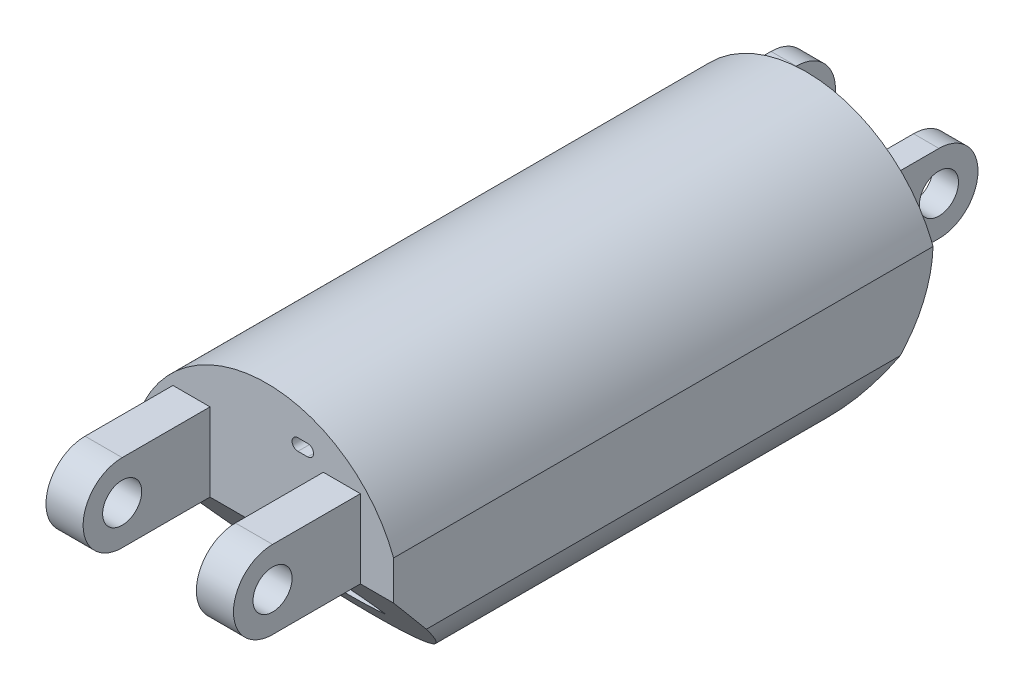
SolidWorks part; units mm, degrees
material "PET"
ref_plane "Front Plane" through (0, 0, 0) normal (0, 0, 1) x (1, 0, 0)
ref_plane "Top Plane" through (0, 0, 0) normal (0, 1, 0) x (1, 0, 0)
ref_plane "Right Plane" through (0, 0, 0) normal (1, 0, 0) x (0, 0, -1)
sketch "Sketch1" plane through (0, 0, 0) normal (0, 0, 1) x (1, 0, 0)
  line L0 (0, 0) -> (0, 5.08)
  line L3 (16.51, 5.08) -> (16.51, 0)
  arc A2 (0, 5.08) -> (16.51, 5.08) centre (8.255, 1.9756) cw
  arc A3 (0, 0) -> (16.51, 0) centre (8.255, 3.1044) ccw
  point P7 (8.255, -5.715)
  point P8 (8.255, 10.795)
extrude "Boss-Extrude1" add sketch "Sketch1" along normal mid plane 35.0838 contours A2 L3 A3 L0
sketch "Sketch2" plane through (0, 0, 0) normal (1, 0, 0) x (0, 0, -1)
  line L4 (15.875, 2.54) -> (-49984.125, 2.54) construction
  line L5 (17.5419, 5.08) -> (17.5419, 0) construction
  line L6 (-17.5419, 5.08) -> (-17.5419, 0) construction
  line L10 (0, -1000) -> (0, 49000) construction
  line L17 (-17.5419, 0) -> (-17.5419, 5.08) construction
  line L23 (17.5419, -5.715) -> (10.6151, -5.715)
  line L24 (17.5419, 2.54) -> (17.5419, -5.715)
  line L30 (-17.5419, 2.54) -> (-17.5419, -5.715)
  line L32 (-17.5419, -5.715) -> (-10.6151, -5.715)
  line L33 (-17.5419, -5.715) -> (17.5419, -5.715) construction
  line L34 (-10.6151, -5.715) -> (-17.5419, 2.54)
  line L35 (10.6151, -5.715) -> (17.5419, 2.54)
  line L36 (-17.5419, -5.715) -> (17.5419, -5.715) construction
  point P0 (-15.0884, 2.54)
  point P11 (17.5419, 2.54)
  point P14 (-17.5419, 2.54)
  dimension "D4" = 50
extrude "Cut-Extrude1" cut sketch "Sketch2" along normal through all
sketch "Sketch3" plane through (0, 0, 17.5419) normal (0, 0, 1) x (1, 0, 0)
  arc A0 (16.51, 5.08) -> (0, 5.08) centre (8.255, 1.9756) ccw construction
  arc A3 (16.51, 5.08) -> (0, 5.08) centre (8.255, 1.9756) ccw
  arc A5 (15.3213, 4.633) -> (1.1887, 4.633) centre (8.255, 1.9756) ccw
  arc A6 (5.024, 8.7987) -> (11.3659, 8.8543) centre (8.1936, 8.985) ccw
  arc A7 (14.9144, 0.2378) -> (1.7305, 0.2378) centre (8.3225, 3.9175) cw
  arc A9 (5.2791, -2.9913) -> (11.3659, -2.9913) centre (8.3225, -3.8959) cw
  dimension "D2" = 1.27
  dimension "D4" = 3.175
extrude "Cut-Extrude2" cut sketch "Sketch3" against normal through all
ref_plane "Plane1" through (11.43, 0, 0) normal (1, 0, 0) x (0, 0, -1)
sketch "Sketch4" plane through (11.43, 0, 0) normal (1, 0, 0) x (0, 0, -1)
  line L0 (-17.5419, 7.62) -> (-20.7169, 7.62)
  line L1 (-17.5419, 7.62) -> (-17.5419, 2.54)
  line L2 (-17.5419, 2.54) -> (-20.7169, 2.54)
  line L3 (-17.5419, 5.08) -> (-17.5419, 2.54) construction
  line L4 (-15.4106, 0) -> (15.4106, 0) construction
  arc A0 (-20.7169, 7.62) -> (-20.7169, 2.54) centre (-20.7169, 5.08) ccw
  circle A1 centre (-20.7169, 5.08) radius 1.27
  dimension "D2" = 2.54
  dimension "D1" = 5.08
  dimension "D3" = 3.175
  dimension "D4" = 2.54
extrude "Boss-Extrude2" add sketch "Sketch4" along normal mid plane 1.27
sketch "Sketch5" plane through (10.795, 0, 0) normal (-1, 0, 0) x (0, 0, 1)
  line L3 (17.5419, 7.62) -> (17.5419, 2.54)
  line L4 (17.5419, 2.54) -> (20.7169, 2.54)
  line L5 (20.7169, 7.62) -> (17.5419, 7.62)
  line L6 (17.5419, 7.62) -> (17.5419, 2.54)
  line L7 (17.5419, 2.54) -> (20.7169, 2.54)
  line L8 (20.7169, 7.62) -> (17.5419, 7.62)
  circle A0 centre (20.7169, 5.08) radius 1.27 construction
  arc A1 (20.7169, 2.54) -> (20.7169, 7.62) centre (20.7169, 5.08) ccw
  arc A2 (20.7169, 2.54) -> (20.7169, 7.62) centre (20.7169, 5.08) ccw
  circle A3 centre (20.7169, 5.08) radius 1.27
  dimension "D1" = 0
extrude "Boss-Extrude3" add sketch "Sketch5" along normal blind 1.27
ref_plane "Plane2" through (8.255, 0, 0) normal (1, 0, 0) x (0, 0, -1)
mirror "Mirror1" about plane through (8.255, 0, 0) normal (1, 0, 0) of "Boss-Extrude3", "Boss-Extrude2"
mirror "Mirror2" about plane through (0, 0, 0) normal (0, 0, 1) of "Mirror1", "Boss-Extrude3", "Boss-Extrude2"
sketch "Sketch6" plane through (9.525, 0, 0) normal (-1, 0, 0) x (0, 0, 1)
  line L3 (20.7169, 7.62) -> (17.5419, 7.62)
  line L4 (17.5419, 7.62) -> (17.5419, 2.54)
  line L5 (17.5419, 2.54) -> (20.7169, 2.54)
  line L6 (20.7169, 7.62) -> (17.5419, 7.62)
  line L7 (17.5419, 7.62) -> (17.5419, 2.54)
  line L8 (17.5419, 2.54) -> (20.7169, 2.54)
  circle A0 centre (20.7169, 5.08) radius 1.27 construction
  arc A1 (20.7169, 2.54) -> (20.7169, 7.62) centre (20.7169, 5.08) ccw
  arc A2 (20.7169, 2.54) -> (20.7169, 7.62) centre (20.7169, 5.08) ccw
  circle A3 centre (20.7169, 5.08) radius 1.27
  dimension "D1" = 0
extrude "Cut-Extrude3" cut sketch "Sketch6" against normal blind 0.635
sketch "Sketch7" plane through (12.065, 0, 0) normal (1, 0, 0) x (0, 0, -1)
  line L3 (-17.5419, 2.54) -> (-17.5419, 7.62)
  line L4 (-17.5419, 7.62) -> (-20.7169, 7.62)
  line L5 (-20.7169, 2.54) -> (-17.5419, 2.54)
  line L6 (-17.5419, 2.54) -> (-17.5419, 7.62)
  line L7 (-17.5419, 7.62) -> (-20.7169, 7.62)
  line L8 (-20.7169, 2.54) -> (-17.5419, 2.54)
  circle A0 centre (-20.7169, 5.08) radius 1.27 construction
  arc A1 (-20.7169, 7.62) -> (-20.7169, 2.54) centre (-20.7169, 5.08) ccw
  arc A2 (-20.7169, 7.62) -> (-20.7169, 2.54) centre (-20.7169, 5.08) ccw
  circle A3 centre (-20.7169, 5.08) radius 1.27
  dimension "D1" = 0
extrude "Boss-Extrude4" add sketch "Sketch7" along normal blind 0.381
mirror "Mirror3" about plane through (8.255, 0, 0) normal (1, 0, 0) of "Boss-Extrude4", "Cut-Extrude3"
mirror "Mirror4" about plane through (0, 0, 0) normal (0, 0, 1) of "Mirror3", "Cut-Extrude3", "Boss-Extrude4"
sketch "Sketch13" plane through (12.446, 0, 0) normal (1, 0, 0) x (0, 0, -1)
  line L0 (-20.7169, 2.54) -> (-17.5419, 2.54) construction
  line L1 (-17.5419, 7.62) -> (-23.2569, 7.62)
  line L2 (-17.5419, 7.62) -> (-17.5419, 2.54)
  line L3 (-17.5419, 2.54) -> (-23.2569, 2.54)
  line L4 (-23.2569, 7.62) -> (-23.2569, 2.54) construction
  arc A0 (-20.7169, 7.62) -> (-20.7169, 2.54) centre (-20.7169, 5.08) ccw construction
  arc A1 (-23.2569, 7.62) -> (-23.2569, 2.54) centre (-23.2569, 5.08) ccw
extrude "Boss-Extrude8" add sketch "Sketch13" against normal up to surface (2.286 mm away) up to face at (10.16, 5.08, 21.9869)
sketch "Sketch14" plane through (4.064, 0, 0) normal (-1, 0, 0) x (0, 0, 1)
  line L3 (17.5419, 2.54) -> (23.2569, 2.54)
  line L5 (17.5419, 7.62) -> (17.5419, 2.54)
  line L8 (17.5419, 7.62) -> (17.5419, 2.54)
  line L13 (17.5419, 2.54) -> (23.2569, 2.54)
  line L15 (23.2569, 7.62) -> (17.5419, 7.62)
  line L16 (23.2569, 7.62) -> (17.5419, 7.62)
  arc A1 (23.2569, 2.54) -> (23.2569, 7.62) centre (23.2569, 5.08) ccw
  arc A6 (23.2569, 2.54) -> (23.2569, 7.62) centre (23.2569, 5.08) ccw
  dimension "D1" = 0
extrude "Boss-Extrude9" add sketch "Sketch14" against normal up to surface (2.286 mm away) up to face at (6.35, 5.08, 19.7644)
ref_plane "Plane3" through (8.255, 0, 0) normal (1, 0, 0) x (0, 0, -1)
sketch "Sketch30" plane through (8.255, 0, 0) normal (1, 0, 0) x (0, 0, -1)
  line L3 (17.5419, 2.54) -> (20.7169, 2.54)
  line L4 (20.7169, 7.62) -> (17.5419, 7.62)
  line L5 (17.5419, 7.62) -> (17.5419, 2.54)
  line L6 (17.5419, 2.54) -> (20.7169, 2.54)
  line L7 (20.7169, 7.62) -> (17.5419, 7.62)
  line L9 (17.5419, 7.62) -> (17.5419, 2.54)
  arc A1 (20.7169, 2.54) -> (20.7169, 7.62) centre (20.7169, 5.08) ccw
  arc A2 (20.7169, 2.54) -> (20.7169, 7.62) centre (20.7169, 5.08) ccw
  circle A3 centre (20.7169, 5.08) radius 1.27
  circle A4 centre (20.7169, 5.08) radius 1.27
  dimension "D1" = 0
  dimension "D2" = 0
extrude "Cut-Extrude13" cut sketch "Sketch30" against normal blind 3.81 and the other way blind 3.81
sketch "Sketch31" plane through (12.446, 0, 0) normal (1, 0, 0) x (0, 0, -1)
  line L3 (17.5419, 2.54) -> (20.7169, 2.54)
  line L4 (20.7169, 7.62) -> (17.5419, 7.62)
  line L5 (17.5419, 7.62) -> (17.5419, 2.54)
  line L6 (17.5419, 2.54) -> (20.7169, 2.54)
  line L7 (20.7169, 7.62) -> (17.5419, 7.62)
  line L9 (17.5419, 7.62) -> (17.5419, 2.54)
  circle A1 centre (20.7169, 5.08) radius 1.27
  circle A2 centre (20.7169, 5.08) radius 1.27
  arc A3 (20.7169, 2.54) -> (20.7169, 7.62) centre (20.7169, 5.08) ccw
  arc A4 (20.7169, 2.54) -> (20.7169, 7.62) centre (20.7169, 5.08) ccw
  dimension "D1" = 0
  dimension "D2" = 0
extrude "Boss-Extrude17" add sketch "Sketch31" along normal blind 1.27
mirror "Mirror11" about plane through (8.255, 0, 0) normal (1, 0, 0) of "Boss-Extrude17"
sketch "Sketch32" plane through (0, 0, -17.5419) normal (0, 0, -1) x (-1, 0, 0)
  line L0 (-16.51, 2.54) -> (-13.716, 2.54) construction
  line L1 (-10.922, 3.048) -> (-5.588, 3.048) construction
  line L2 (-10.922, 3.048) -> (-10.922, 8.7376) construction
  line L3 (-10.922, 8.7376) -> (-5.588, 8.7376) construction
  line L4 (-5.588, 3.048) -> (-5.588, 8.7376) construction
  line L5 (-10.922, 3.048) -> (-5.588, 8.7376) construction
  line L6 (-10.922, 8.7376) -> (-5.588, 3.048) construction
  line L7 (-16.51, 2.54) -> (-13.716, 2.54)
  line L8 (-6.223, 8.3566) -> (-5.588, 8.3566) construction
  line L9 (-6.223, 8.7376) -> (-5.588, 8.7376)
  line L10 (-6.223, 7.9756) -> (-5.588, 7.9756)
  line L11 (-12.065, 2.54) -> (-4.445, 2.54) construction
  arc A0 (-6.223, 8.7376) -> (-6.223, 7.9756) centre (-6.223, 8.3566) ccw
  arc A1 (-5.588, 7.9756) -> (-5.588, 8.7376) centre (-5.588, 8.3566) ccw
  point P0 (-8.255, 5.8928)
  point P11 (-5.9055, 8.3566)
  point P19 (-8.255, 2.54)
  dimension "D1" = 5.6896
  dimension "D2" = 5.334
  dimension "D3" = 3.048
  dimension "D4" = 0.762
  dimension "D5" = 0.635
extrude "Cut-Extrude14" cut sketch "Sketch32" against normal blind 17.78 contours L10 A1 L9 A0
fillet "Fillet1" radius 7.62 2 edges at (1.397, 2.54, -17.5419) (15.113, 2.54, -17.5419)
sketch "Sketch33" plane through (8.255, 0, 0) normal (1, 0, 0) x (0, 0, -1)
  line L3 (-23.2569, 2.54) -> (-17.5419, 2.54)
  line L4 (-17.5419, 2.54) -> (-17.5419, 7.62)
  line L5 (-17.5419, 7.62) -> (-23.2569, 7.62)
  line L6 (-23.2569, 2.54) -> (-17.5419, 2.54)
  line L7 (-17.5419, 2.54) -> (-17.5419, 7.62)
  line L8 (-17.5419, 7.62) -> (-23.2569, 7.62)
  circle A0 centre (-23.2569, 5.08) radius 1.27
  arc A1 (-23.2569, 7.62) -> (-23.2569, 2.54) centre (-23.2569, 5.08) ccw
  arc A5 (-23.2569, 7.62) -> (-23.2569, 2.54) centre (-23.2569, 5.08) ccw
  dimension "D2" = 2.54
  dimension "D1" = 0
extrude "Boss-Extrude18" add sketch "Sketch33" against normal blind 6.096 and the other way blind 6.096
sketch "Sketch34" plane through (0, 0, 17.5419) normal (0, 0, 1) x (1, 0, 0)
  line L0 (14.351, 7.62) -> (2.159, 7.62) construction
  line L1 (4.572, 7.62) -> (11.938, 7.62)
  line L2 (4.572, 7.62) -> (4.572, 1.7045)
  line L3 (4.572, 1.7045) -> (11.938, 1.7045)
  line L4 (11.938, 7.62) -> (11.938, 1.7045)
  line L5 (14.351, 2.54) -> (14.351, 7.62) construction
  line L6 (2.159, 7.62) -> (2.159, 2.54) construction
  dimension "D1" = 2.413
  dimension "D2" = 2.413
extrude "Cut-Extrude15" cut sketch "Sketch34" along normal through all
sketch "Sketch35" plane through (14.351, 0, 0) normal (1, 0, 0) x (0, 0, -1)
  circle A0 centre (-23.2569, 5.08) radius 1.27 construction
  circle A1 centre (-23.2569, 5.08) radius 1.27
extrude "Cut-Extrude16" cut sketch "Sketch35" against normal through all both and the other way through all
sketch "Sketch36" plane through (0, 0, 0) normal (-1, 0, 0) x (0, 0, 1)
  text T0 "Ring 3\r\n"
extrude "Cut-Extrude17" cut sketch "Sketch36" against normal blind 1
sketch "Sketch37" plane through (0, 0, 17.5419) normal (0, 0, 1) x (1, 0, 0)
  line L0 (11.938, 2.54) -> (4.572, 2.54) construction
  line L1 (5.588, 8.7376) -> (10.922, 8.7376)
  line L2 (5.588, 8.7376) -> (5.588, 3.048)
  line L3 (5.588, 3.048) -> (10.922, 3.048)
  line L4 (10.922, 8.7376) -> (10.922, 3.048)
  line L5 (5.588, 8.7376) -> (10.922, 3.048) construction
  line L6 (5.588, 3.048) -> (10.922, 8.7376) construction
  line L7 (11.938, 2.54) -> (4.572, 2.54)
  line L8 (10.922, 8.3566) -> (10.287, 8.3566) construction
  line L9 (10.922, 7.9756) -> (10.287, 7.9756)
  line L10 (10.922, 8.7376) -> (10.287, 8.7376)
  arc A0 (10.922, 7.9756) -> (10.922, 8.7376) centre (10.922, 8.3566) ccw
  arc A1 (10.287, 8.7376) -> (10.287, 7.9756) centre (10.287, 8.3566) ccw
  point P0 (8.255, 5.8928)
  point P7 (8.255, 2.54)
  point P8 (8.255, 3.048)
  point P12 (10.6045, 8.3566)
  dimension "D1" = 5.6896
  dimension "D2" = 5.334
  dimension "D3" = 3.048
  dimension "D4" = 0.635
  dimension "D5" = 0.762
extrude "Cut-Extrude18" cut sketch "Sketch37" against normal blind 22.86 contours L1 A1 L9 L4 | L4 A0
equation "\"D1@Sketch1\"=.65"
equation "\"D2@Sketch1\"=.65"
equation "\"D1@Boss-Extrude1\"=2.125*.65"
